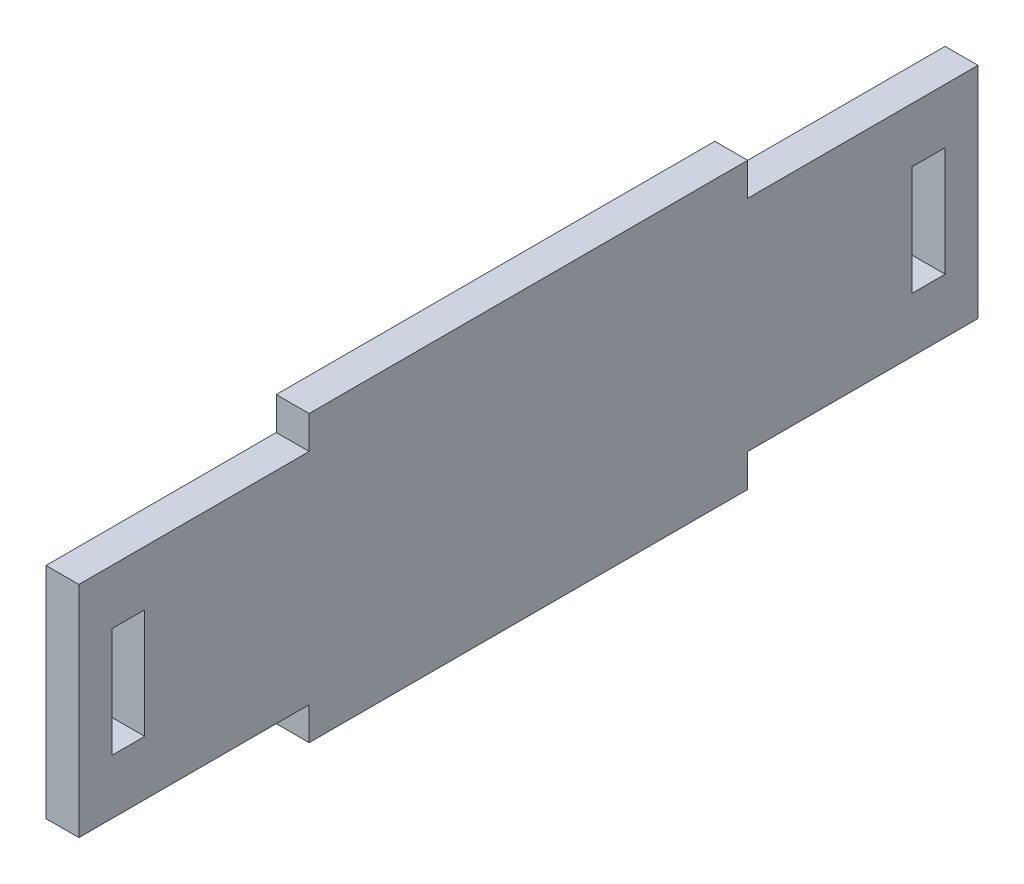
SolidWorks part; units mm, degrees
ref_plane "Front Plane" through (0, 0, 0) normal (0, 0, 1) x (1, 0, 0)
ref_plane "Top Plane" through (0, 0, 0) normal (0, 1, 0) x (1, 0, 0)
ref_plane "Right Plane" through (0, 0, 0) normal (1, 0, 0) x (0, 0, -1)
sketch "Sketch1" plane through (0, 0, 0) normal (1, 0, 0) x (0, 0, -1)
  line L0 (0, 0) -> (-6, 0) construction
  line L1 (0, 0) -> (70, 0) construction
  line L2 (0, 0) -> (0, 20) construction
  line L3 (0, 20) -> (70, 20) construction
  line L4 (70, 0) -> (70, 20) construction
  line L5 (70, 20) -> (76, 20) construction
  line L6 (0, 10) -> (-1.5, 10) construction
  line L11 (70, 10) -> (71.5, 10) construction
  line L12 (-3, 15) -> (0, 15)
  line L13 (-3, 15) -> (-3, 5)
  line L14 (-3, 5) -> (0, 5)
  line L15 (0, 15) -> (0, 5)
  line L16 (-3, 15) -> (0, 5) construction
  line L17 (-3, 5) -> (0, 15) construction
  line L18 (35, 20) -> (35, 21.5) construction
  line L19 (73, 15) -> (70, 15)
  line L20 (73, 15) -> (73, 5)
  line L21 (73, 5) -> (70, 5)
  line L22 (70, 15) -> (70, 5)
  line L23 (73, 15) -> (70, 5) construction
  line L24 (73, 5) -> (70, 15) construction
  line L25 (35, 0) -> (35, -1.5) construction
  line L26 (-6, 0) -> (-6, 20)
  line L27 (15, 23) -> (55, 23) construction
  line L28 (15, 23) -> (15, 20) construction
  line L29 (15, 20) -> (55, 20) construction
  line L30 (55, 23) -> (55, 20) construction
  line L31 (15, 23) -> (55, 20) construction
  line L32 (15, 20) -> (55, 23) construction
  line L33 (15, -3) -> (55, -3) construction
  line L34 (15, -3) -> (15, 0) construction
  line L35 (15, 0) -> (55, 0) construction
  line L36 (55, -3) -> (55, 0) construction
  line L37 (15, -3) -> (55, 0) construction
  line L38 (15, 0) -> (55, -3) construction
  line L39 (-6, 20) -> (15, 20)
  line L40 (15, 20) -> (15, 23)
  line L41 (15, 23) -> (55, 23)
  line L42 (55, 23) -> (55, 20)
  line L43 (55, 20) -> (76, 20)
  line L44 (76, 20) -> (76, 0)
  line L45 (76, 0) -> (55, 0)
  line L46 (55, -3) -> (15, -3)
  line L47 (15, 0) -> (-6, 0)
  line L48 (55, 0) -> (55, -3)
  line L49 (15, 0) -> (15, -3)
extrude "Boss-Extrude1" add sketch "Sketch1" along normal blind 3
